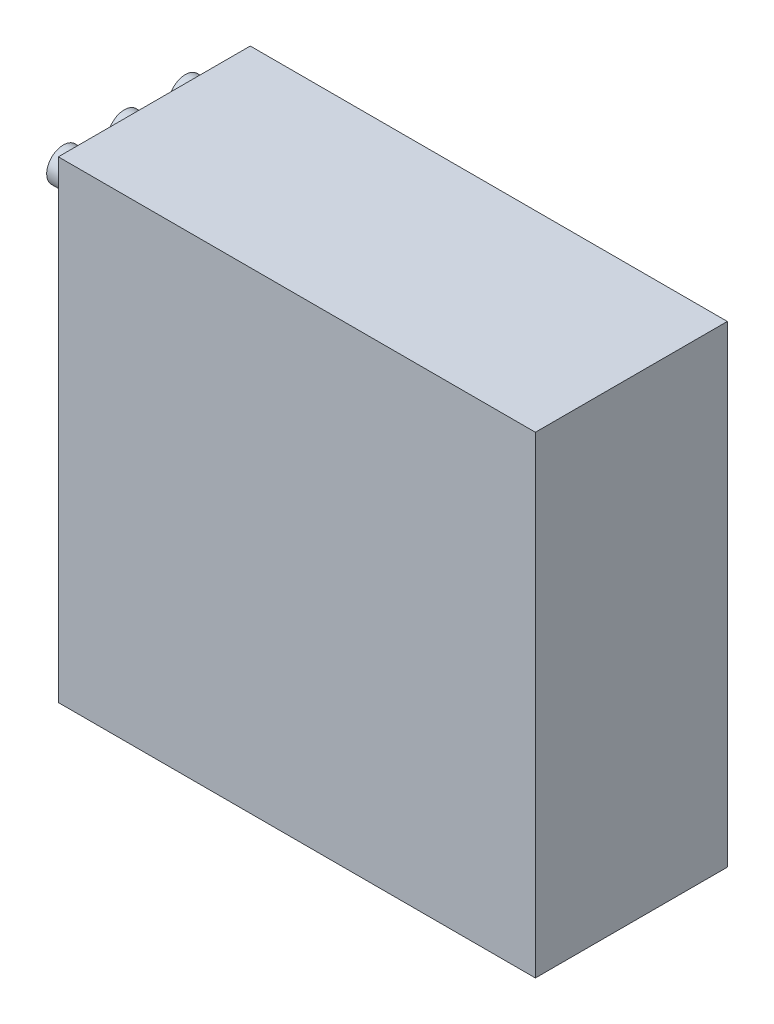
SolidWorks part; units mm, degrees
ref_plane "Front Plane" through (0, 0, 0) normal (0, 0, 1) x (1, 0, 0)
ref_plane "Top Plane" through (0, 0, 0) normal (0, 1, 0) x (1, 0, 0)
ref_plane "Right Plane" through (0, 0, 0) normal (1, 0, 0) x (0, 0, -1)
sketch "Sketch1" plane through (0, 0, 0) normal (0, 0, 1) x (1, 0, 0)
  line L0 (0, 0) -> (430, 0)
  line L1 (430, 0) -> (430, 426)
  line L2 (430, 426) -> (0, 426)
  line L3 (0, 426) -> (0, 0)
  dimension "D1" = 430
  dimension "D2" = 426
extrude "Boss-Extrude1" add sketch "Sketch1" along normal blind 173
sketch "Sketch2" plane through (0, 0, 0) normal (-1, 0, 0) x (0, 0, 1)
  line L0 (86.5, 426) -> (86.5, 391)
  line L1 (173, 426) -> (0, 426) construction
  line L2 (86.5, 391) -> (31.5, 391)
  line L3 (86.5, 391) -> (141.5, 391)
  circle A0 centre (86.5, 391) radius 15
  circle A1 centre (31.5, 391) radius 15
  circle A2 centre (141.5, 391) radius 15
  dimension "D4" = 30
  dimension "D5" = 30
  dimension "D6" = 30
  dimension "D1" = 35
  dimension "D2" = 55
  dimension "D3" = 55
extrude "Boss-Extrude2" add sketch "Sketch2" along normal blind 27
